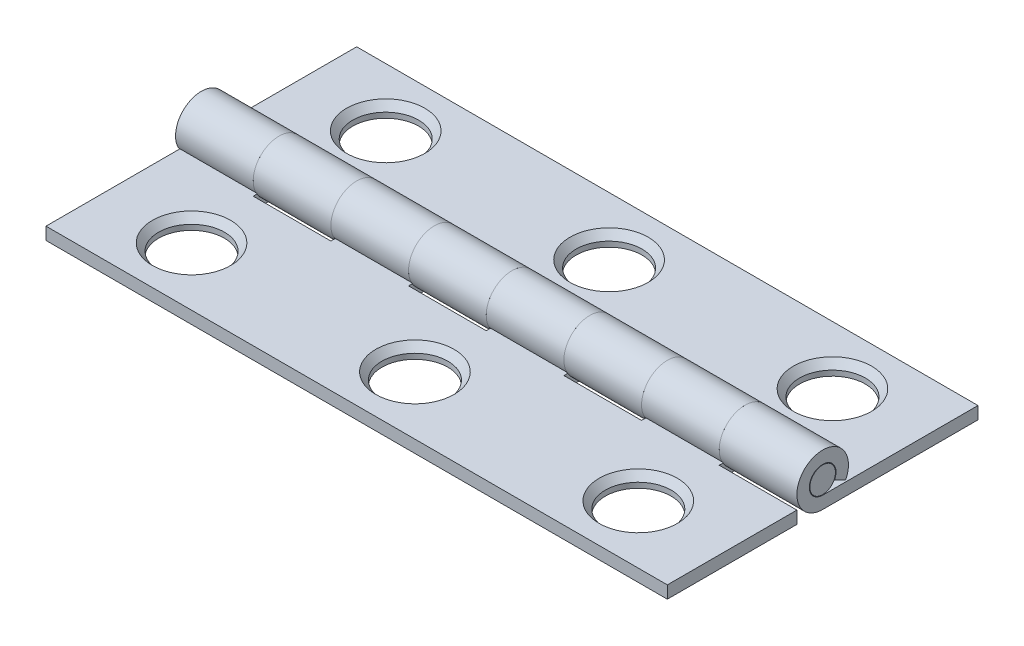
SolidWorks part; units mm, degrees
ref_plane "Front Plane" through (0, 0, 0) normal (0, 0, 1) x (1, 0, 0)
ref_plane "Top Plane" through (0, 0, 0) normal (0, 1, 0) x (1, 0, 0)
ref_plane "Right Plane" through (0, 0, 0) normal (1, 0, 0) x (0, 0, -1)
sketch "Sketch1" plane through (0, 0, 0) normal (0, 1, 0) x (1, 0, 0)
  line L0 (-25.4, 0) -> (25.4, 0) construction
  line L1 (-25.4, -12.7) -> (-25.4, 12.7) construction
  line L2 (-25.4, -12.7) -> (-18.2626, -12.7) construction
  line L3 (-18.2626, -12.7) -> (0, -12.7) construction
  line L4 (0, -12.7) -> (18.2626, -12.7) construction
  line L5 (25.4, -12.7) -> (25.4, -7.9375) construction
  line L6 (18.2626, -12.7) -> (25.4, -12.7) construction
  line L7 (-25.4, 12.7) -> (-18.2626, 12.7) construction
  line L8 (-18.2626, 12.7) -> (0, 12.7) construction
  line L9 (0, 12.7) -> (18.2626, 12.7) construction
  line L10 (18.2626, 12.7) -> (25.4, 12.7) construction
  line L11 (18.2626, -11.1379) -> (18.2626, -4.7371) construction
  line L12 (18.2626, -7.9375) -> (25.4, -7.9375) construction
  point P3 (18.2626, -10.6299)
  point P4 (0, 0)
  point P8 (-25.4, 0)
  point P17 (-19.05, 0)
  point P21 (18.2626, -7.9375)
  dimension "Frame Leaf Height" = 50.8
  dimension "Overall Width" = 25.4
  dimension "Hole to End 1" = 7.1374
  dimension "Hole Spacing" = 18.2626
  dimension "D3" = 18.2626
  dimension "Hole to End 2" = 7.1374
  dimension "D1" = 7.1374
  dimension "D2" = 7.1374
  dimension "D4" = 18.2626
  dimension "D6" = 18.2626
  dimension "Knuckle Length" = 6.35
  dimension "Hole Chamfer Dia" = 6.4008
  dimension "Hole Center to Pin" = 7.9375
  dimension "Door Leaf Height" = 50.8
  dimension "Frame Leaf Width" = 12.7
  dimension "Door Leaf Width" = 12.7
  dimension "Mounting Hole Diameter" = 5.3848
sketch "Sketch2" plane through (0, 0, 0) normal (1, 0, 0) x (0, 0, -1)
  line L2 (0, -2.1082) -> (0, -1.0922) construction
  line L4 (0, 1.0922) -> (0, -1.0922) construction
  point P8 (0, 0)
  dimension "Leaf Thickness" = 1.016
  dimension "Pin Diameter" = 2.1844
sketch "Sketch3" plane through (0, 0, 0) normal (1, 0, 0) x (0, 0, -1)
  line L3 (0, 0) -> (-2.1082, -1.0922) construction
  line L4 (0, -2.1082) -> (-12.7, -2.1082)
  line L5 (-12.7, -2.1082) -> (-12.7, -1.0922)
  line L7 (-12.7, -1.0922) -> (0, -1.0922)
  line L8 (-12.7, 0) -> (12.7, 0) construction
  line L9 (-0.9698, -0.5024) -> (-1.8719, -0.9698)
  line L11 (-2.1082, 0) -> (-2.1082, -1.0922) construction
  circle A4 centre (0, 0) radius 1.0922 construction
  circle A5 centre (0, 0) radius 2.1082 construction
  arc A8 (-0.9698, -0.5024) -> (0, -1.0922) centre (0, 0) cw
  arc A9 (-1.8719, -0.9698) -> (0, -2.1082) centre (0, 0) cw
  point P0 (-1.8719, -0.9698)
  point P13 (-0.9698, -0.5024)
extrude "Boss-Extrude1" add sketch "Sketch3" along normal mid plane 50.8
sketch "Sketch4" plane through (0, 0, 0) normal (0, 1, 0) x (1, 0, 0)
  line L0 (-25.4, -2.1082) -> (25.4, -2.1082) construction
  line L1 (-25.4, -2.1082) -> (25.4, -2.1082) construction
  line L2 (25.4, 2.1082) -> (-25.4, 2.1082) construction
  line L3 (25.4, 2.1082) -> (-25.4, 2.1082) construction
  line L4 (-19.05, -2.1082) -> (-19.05, 2.1082)
  line L6 (-19.05, 2.1082) -> (-12.7, 2.1082)
  line L7 (-12.7, -2.1082) -> (-19.05, -2.1082)
  line L8 (-12.7, 2.1082) -> (-12.7, -2.1082)
  point P8 (-19.05, 0)
  dimension "D1" = 6.35
extrude "Cut-Extrude1" cut sketch "Sketch4" against normal through all both and the other way through all
pattern_linear "LPattern1" count 6 spacing 12.7 along (1, 0, 0) of "Cut-Extrude1"
sketch "Sketch5" plane through (0, -1.0922, 0) normal (0, 1, 0) x (1, 0, 0)
  line L0 (18.2626, -7.9375) -> (-18.2626, -7.9375) construction
  line L1 (0, -7.9375) -> (0, -12.7) construction
  line L2 (-18.2626, -7.9375) -> (-18.2626, -12.7) construction
  circle A0 centre (18.2626, -7.9375) radius 3.2004
  circle A1 centre (0, -7.9375) radius 3.2004
  circle A2 centre (-18.2626, -7.9375) radius 3.2004
extrude "Cut-Extrude2" cut sketch "Sketch5" against normal through all draft 41
sketch "Sketch9" plane through (0, 0, 0) normal (0, 1, 0) x (1, 0, 0)
  circle A0 centre (18.2626, -7.9375) radius 2.6924
  circle A1 centre (0, -7.9375) radius 2.6924
  circle A2 centre (-18.2626, -7.9375) radius 2.6924
  dimension "D1" = 5.3848
extrude "Cut-Extrude3" cut sketch "Sketch9" against normal through all both and the other way through all
pattern_circular "CirPattern1" count 2 over 360 about axis through (0, 0, 0) along (0, 1, 0) of bodies 110 107
sketch "Sketch6" plane through (0, 0, 0) normal (1, 0, 0) x (0, 0, -1)
  circle A0 centre (0, 0) radius 1.0922
  dimension "D1" = 2.1844
extrude "Boss-Extrude2" add sketch "Sketch6" along normal mid plane 50.8 separate body
chamfer "Chamfer1" distance 0.0437 angle 45 2 edges at (25.4, 0, -1.0922) (-25.4, 0, -1.0922)
sketch "Sketch7" plane through (0, 0, 0) normal (1, 0, 0) x (0, 0, -1)
  line L0 (-1.0922, 0) -> (1.0922, 0) construction
  line L1 (-12.7, 0) -> (12.7, 0) construction
  line L2 (12.7, -1.0922) -> (12.7, -2.1082) construction
  line L3 (12.7, -1.0922) -> (12.7, -2.1082) construction
  line L4 (12.7, -2.1082) -> (-12.7, -2.1082) construction
  line L5 (-12.7, -2.1082) -> (-12.7, -1.0922)
  point P6 (0, 0)
  point P8 (1.0922, 0)
  point P9 (-1.0922, 0)
  point P12 (12.7, -1.0922)
  point P13 (12.7, -2.1082)
  point P14 (-12.7, -2.1082)
  dimension "D1" = 2.1844
  dimension "D2" = 25.4
  dimension "D3" = 1.016
sketch "Sketch8" plane through (0, 0, 0) normal (0, 1, 0) x (1, 0, 0)
  line L0 (-21.463, -7.9375) -> (-15.0622, -7.9375) construction
  line L1 (-3.2004, -7.9375) -> (3.2004, -7.9375) construction
  line L2 (15.0622, -7.9375) -> (21.463, -7.9375) construction
  line L3 (-18.2626, -4.7371) -> (-18.2626, -11.1379) construction
  line L4 (0, -4.7371) -> (0, -11.1379) construction
  line L5 (18.2626, -4.7371) -> (18.2626, -11.1379) construction
  line L6 (-18.2626, 11.1379) -> (-18.2626, 4.7371) construction
  line L7 (-21.463, 7.9375) -> (-15.0622, 7.9375) construction
  line L8 (0, 11.1379) -> (0, 4.7371) construction
  line L9 (-3.2004, 7.9375) -> (3.2004, 7.9375) construction
  line L10 (18.2626, 11.1379) -> (18.2626, 4.7371) construction
  line L11 (15.0622, 7.9375) -> (21.463, 7.9375) construction
  line L12 (18.2626, 7.9375) -> (20.5256, 10.2005) construction
  circle A1 centre (-18.2626, -7.9375) radius 3.2004 construction
  circle A2 centre (0, -7.9375) radius 3.2004 construction
  circle A3 centre (18.2626, -7.9375) radius 3.2004 construction
  circle A4 centre (-18.2626, 7.9375) radius 3.2004 construction
  circle A5 centre (0, 7.9375) radius 3.2004 construction
  circle A6 centre (18.2626, 7.9375) radius 3.2004 construction
  circle A7 centre (18.2626, 7.9375) radius 3.2004 construction
  point P2 (-25.4, 0)
  point P7 (-18.2626, -7.9375)
  point P13 (0, -7.9375)
  point P19 (18.2626, -7.9375)
  point P25 (-25.4, 12.7)
  point P26 (25.4, 12.7)
  point P28 (-25.4, -12.7)
  point P30 (25.4, -12.7)
  point P32 (-21.463, -7.9375)
  point P33 (-18.2626, -4.7371)
  point P34 (-15.0622, -7.9375)
  point P35 (-18.2626, -11.1379)
  point P36 (0, -11.1379)
  point P37 (-3.2004, -7.9375)
  point P38 (0, -4.7371)
  point P39 (3.2004, -7.9375)
  point P40 (21.463, -7.9375)
  point P41 (18.2626, -11.1379)
  point P42 (15.0622, -7.9375)
  point P43 (18.2626, -4.7371)
  point P66 (0, -12.7)
  point P67 (18.2626, -12.7)
  point P69 (-18.2626, -12.7)
  point P71 (-18.2626, 12.7)
  point P73 (-18.2626, 7.9375)
  point P75 (0, 7.9375)
  point P76 (18.2626, 7.9375)
  point P77 (18.2626, 12.7)
  point P78 (0, 12.7)
  point P82 (-18.2626, 11.1379)
  point P83 (-21.463, 7.9375)
  point P84 (-18.2626, 4.7371)
  point P85 (-15.0622, 7.9375)
  point P86 (0, 4.7371)
  point P87 (-3.2004, 7.9375)
  point P88 (0, 11.1379)
  point P89 (3.2004, 7.9375)
  point P90 (18.2626, 4.7371)
  point P91 (15.0622, 7.9375)
  point P92 (18.2626, 11.1379)
  point P93 (21.463, 7.9375)
  point P97 (20.5256, 10.2005)
  dimension "D1" = 45
other "Save Bodies1"
equation "\"D3@Sketch1\"=\"Hole Spacing@Sketch1\""
equation "\"D1@Sketch1\"=\"Hole to End 1@Sketch1\""
equation "\"D2@Sketch1\"=\"Hole to End 2@Sketch1\""
equation "\"D4@Sketch1\"=\"Hole Spacing@Sketch1\""
equation "\"D6@Sketch1\"=\"D4@Sketch1\""
equation "\"D1@Boss-Extrude1\" = \"Frame Leaf Height@Sketch1\""
equation "\"D1@Sketch4\"=\"Knuckle Length@Sketch1\""
equation "\"D3@LPattern1\"=\"Knuckle Length@Sketch1\"*2"
equation "\"D1@Sketch6\"=\"Pin Diameter@Sketch2\""
equation "\"D1@Boss-Extrude2\" = \"Frame Leaf Height@Sketch1\""
equation "\"D1@Sketch7\"=\"Pin Diameter@Sketch2\""
equation "\"D2@Sketch7\"=\"Overall Width@Sketch1\""
equation "\"D3@Sketch7\"=\"Leaf Thickness@Sketch2\""
equation "\"Knuckle Length@Sketch1\" = \"Frame Leaf Height@Sketch1\" / 8"
equation "\"Hole to End 2@Sketch1\"=\"Hole to End 1@Sketch1\""
equation "\"D1@Sketch9\"=\"Mounting Hole Diameter@Sketch1\""
equation "\"D1@Chamfer1\"=\"Pin Diameter@Sketch2\"*.02"
